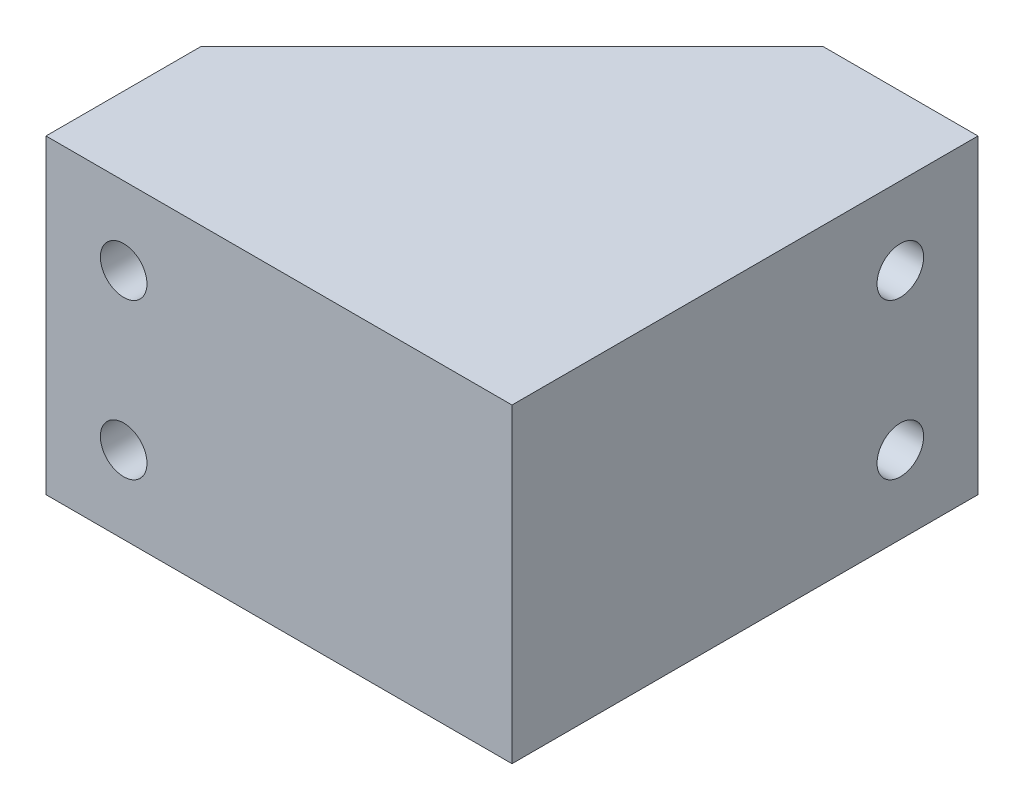
SolidWorks part; units mm, degrees
ref_plane "Front Plane" through (0, 0, 0) normal (0, 0, 1) x (1, 0, 0)
ref_plane "Top Plane" through (0, 0, 0) normal (0, 1, 0) x (1, 0, 0)
ref_plane "Right Plane" through (0, 0, 0) normal (1, 0, 0) x (0, 0, -1)
sketch "Sketch1" plane through (0, 0, 0) normal (0, 1, 0) x (1, 0, 0)
  line L0 (-9.5478, -2.6496) -> (3.1522, 10.0504)
  line L1 (9.5022, 10.0504) -> (9.5022, -8.9996)
  line L2 (9.5022, -8.9996) -> (-9.5478, -8.9996)
  line L3 (-9.5478, -8.9996) -> (-9.5478, -2.6496)
  line L4 (3.1522, 10.0504) -> (9.5022, 10.0504)
  line L5 (-15.8978, -8.9996) -> (-9.5478, -2.6496) construction
  line L6 (-9.5478, -8.9996) -> (-15.8978, -8.9996) construction
  line L7 (3.1522, 10.0504) -> (9.5022, 16.4004) construction
  line L8 (9.5022, 16.4004) -> (9.5022, 10.0504) construction
  dimension "D1" = 25.4
  dimension "D2" = 25.4
  dimension "D3" = 19.05
  dimension "D4" = 19.05
extrude "Boss-Extrude1" add sketch "Sketch1" along normal mid plane 12.7
sketch "Sketch2" plane through (9.5022, 0, 0) normal (1, 0, 0) x (0, 0, -1)
  line L0 (-8.9996, 0) -> (10.0504, 0) construction
  line L1 (-8.9996, 6.35) -> (-8.9996, -6.35) construction
  line L2 (10.0504, 6.35) -> (10.0504, -6.35) construction
  circle A0 centre (6.8754, 3.175) radius 0.9525
  circle A1 centre (6.8754, -3.175) radius 0.9525
  dimension "D1" = 1.905
  dimension "D2" = 6.35
  dimension "D3" = 15.875
extrude "Cut-Extrude1" cut sketch "Sketch2" against normal through all
sketch "Sketch3" plane through (0, 0, 8.9996) normal (0, 0, 1) x (1, 0, 0)
  line L0 (-9.5478, 0) -> (9.5022, 0) construction
  line L1 (-9.5478, 6.35) -> (-9.5478, -6.35) construction
  line L2 (9.5022, 6.35) -> (9.5022, -6.35) construction
  circle A0 centre (-6.3728, 3.175) radius 0.9525
  circle A1 centre (-6.3728, -3.175) radius 0.9525
  dimension "D1" = 1.905
  dimension "D2" = 6.35
  dimension "D3" = 15.875
extrude "Cut-Extrude2" cut sketch "Sketch3" against normal through all
